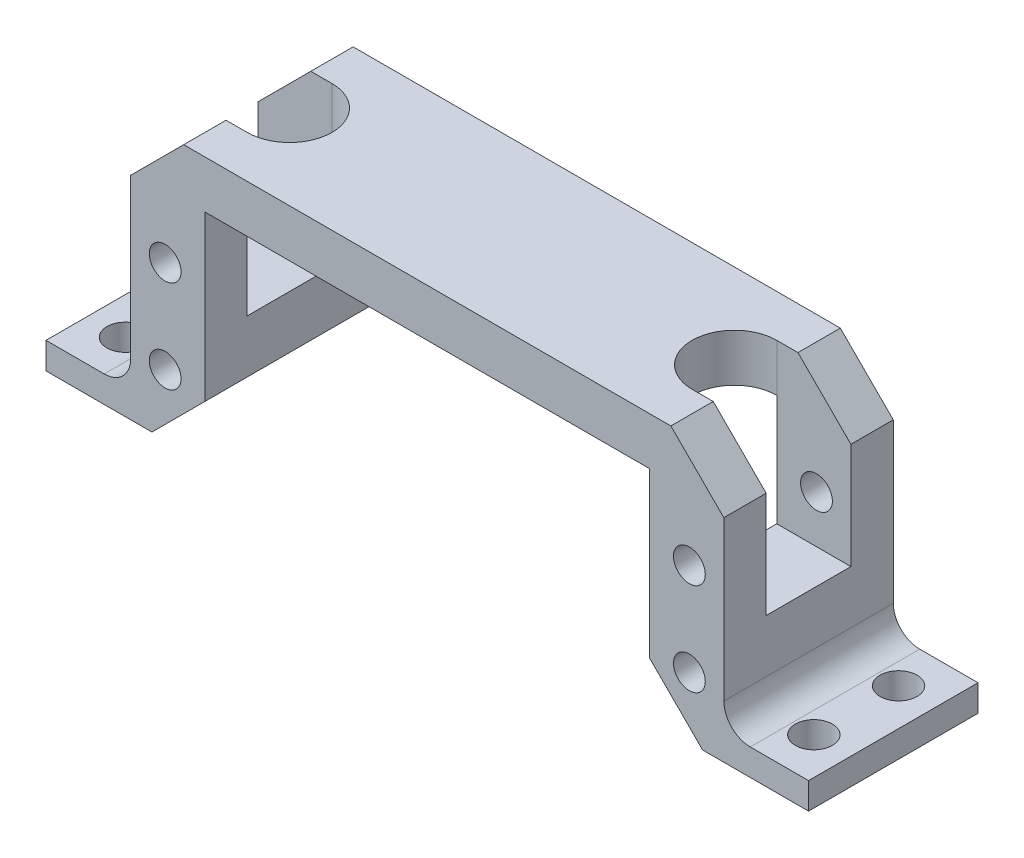
SolidWorks part; units mm, degrees
other "Markup1"
sketch "Sketch6" plane through (-36, 25, 8) normal (-0.8707, 0.2235, 0.4381) x (0.4473, -0.0107, 0.8943)
material "Nylon PA 12"
ref_plane "Front Plane" through (0, 0, 0) normal (0, 0, 1) x (1, 0, 0)
ref_plane "Top Plane" through (0, 0, 0) normal (0, 1, 0) x (1, 0, 0)
ref_plane "Right Plane" through (0, 0, 0) normal (1, 0, 0) x (0, 0, -1)
sketch "Sketch1" plane through (0, 0, 0) normal (0, 0, 1) x (1, 0, 0)
  line L0 (-36, 0) -> (-21, 0)
  line L1 (-21, 0) -> (-21, 20.5)
  line L2 (-21, 20.5) -> (21, 20.5)
  line L3 (21, 20.5) -> (21, 0)
  line L4 (21, 0) -> (36, 0)
  line L5 (-36, 0) -> (-36, 2.5)
  line L6 (-36, 2.5) -> (-28, 2.5)
  line L7 (36, 0) -> (36, 2.5)
  line L8 (36, 2.5) -> (28, 2.5)
  line L9 (-28, 2.5) -> (-28, 25)
  line L10 (-28, 25) -> (28, 25)
  line L11 (28, 25) -> (28, 2.5)
  dimension "D1" = 72
  dimension "D2" = 36
  dimension "D3" = 42
  dimension "D4" = 21
  dimension "D5" = 20.5
  dimension "D6" = 2.5
  dimension "D7" = 25
  dimension "D8" = 56
extrude "Boss-Extrude1" add sketch "Sketch1" along normal mid plane 16
chamfer "Chamfer5" distance 5 angle 45 4 edges at (-28, 25, 0) (21, 0, 0) (-21, 0, 0) (28, 25, 0)
fillet "Fillet1" radius 2.5 2 edges at (28, 2.5, 0) (-28, 2.5, 0)
sketch "Sketch2" plane through (0, 0, 8) normal (0, 0, 1) x (1, 0, 0)
  circle A0 centre (-24.75, 14.475) radius 1.5
  circle A1 centre (-24.75, 5.725) radius 1.5
  circle A2 centre (24.75, 14.475) radius 1.5
  circle A3 centre (24.75, 5.725) radius 1.5
  dimension "D1" = 3
  dimension "D5" = 14.475
  dimension "D3" = 49.5
  dimension "D4" = 24.75
  dimension "D6" = 8.75
extrude "Cut-Extrude1" cut sketch "Sketch2" against normal through all
sketch "Sketch3" plane through (0, 2.5, 0) normal (0, 1, 0) x (1, 0, 0)
  line L0 (36, -8) -> (36, 8) construction
  line L1 (30.5, 28.8859) -> (30.5, -25.0715) construction
  line L2 (-30.5, 27.8941) -> (-30.5, -24.0796) construction
  line L3 (-30.5, -8) -> (-30.5, 8) construction
  line L4 (30.5, 8) -> (30.5, -8) construction
  line L5 (56.6832, -8) -> (-41.1826, -8) construction
  line L6 (65.7079, 8) -> (-46.658, 8) construction
  line L7 (36, 8) -> (30.5, 8) construction
  line L8 (36, -8) -> (30.5, -8) construction
  line L9 (36, 29.9064) -> (36, -19.7738) construction
  circle A0 centre (32.5, 4) radius 1.75
  circle A1 centre (32.5, -4) radius 1.75
  circle A2 centre (-32.5, 4) radius 1.75
  circle A3 centre (-32.5, -4) radius 1.75
  dimension "D2" = 3.5
  dimension "D3" = 3.5
  dimension "D12" = 3.5
  dimension "D1" = 2
  dimension "D4" = 16
  dimension "D5" = 4
  dimension "D6" = 4
  dimension "D7" = 5.5
  dimension "D8" = 2
  dimension "D9" = 4
  dimension "D10" = 12
  dimension "D11" = 16
  dimension "D13" = 3.5
extrude "Cut-Extrude2" cut sketch "Sketch3" against normal through all
sketch "Sketch5" plane through (0, 25, 0) normal (0, 1, 0) x (1, 0, 0)
  line L0 (-28, -8) -> (-28, 8) construction
  line L6 (-32.5, 4) -> (-28, 4) construction
  line L7 (32.5, 4) -> (32.5, -4) construction
  line L8 (32.5, -4) -> (28, -4) construction
  line L9 (-32.5, -4) -> (-32.5, 4) construction
  line L13 (28, 8) -> (28, -8) construction
  line L18 (-28, -4) -> (-32.5, -4) construction
  line L21 (28, 4) -> (32.5, 4) construction
  line L32 (21, -8) -> (21, 8) construction
  line L33 (28, 4) -> (21, 4)
  line L34 (28, 4) -> (28, -4)
  line L35 (28, -4) -> (21, -4)
  line L36 (21, 4) -> (21, -4)
  line L37 (-21, -8) -> (-21, 8) construction
  line L38 (-28, 4) -> (-21, 4)
  line L39 (-28, 4) -> (-28, -4)
  line L40 (-28, -4) -> (-21, -4)
  line L41 (-21, 4) -> (-21, -4)
extrude "Cut-Extrude3" cut sketch "Sketch5" against normal blind 15
sketch "Sketch7" plane through (0, 25, 0) normal (0, 1, 0) x (1, 0, 0)
  line L0 (-23, 4) -> (-23, -4) construction
  line L1 (-21, -4) -> (-21, 4) construction
  line L2 (21, 4) -> (21, -4) construction
  line L3 (21, 4) -> (21, -4)
  line L4 (-21, 4) -> (-21, -4)
  arc A0 (-21, -4) -> (-21, 4) centre (-21, 0) ccw
  arc A1 (21, 4) -> (21, -4) centre (21, 0) ccw
extrude "Cut-Extrude5" cut sketch "Sketch7" against normal blind 15
